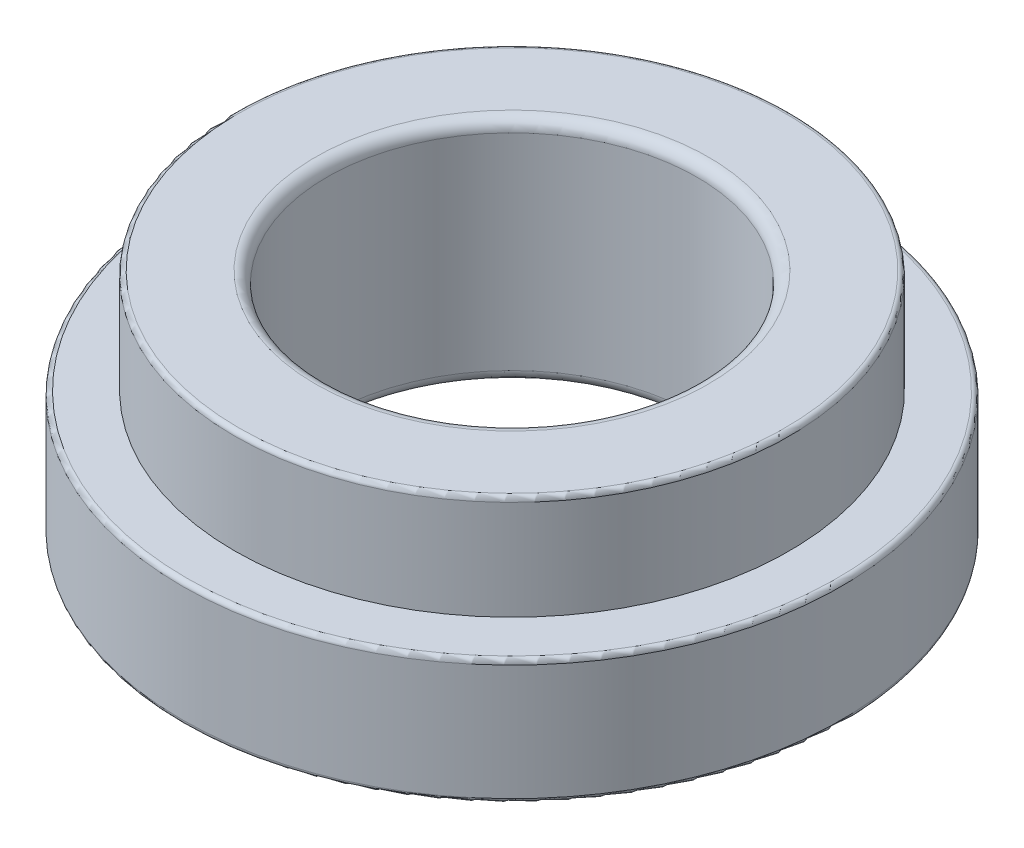
SolidWorks part; units mm, degrees
material "PE High Density"
ref_plane "Front" through (0, 0, 0) normal (0, 0, 1) x (1, 0, 0)
ref_plane "Top" through (0, 0, 0) normal (0, 1, 0) x (1, 0, 0)
ref_plane "Right" through (0, 0, 0) normal (1, 0, 0) x (0, 0, -1)
sketch "Sketch1" plane through (0, 0, 0) normal (0, 1, 0) x (1, 0, 0)
  circle A0 centre (0, 0) radius 7.125
  dimension "D1" = 14.25
extrude "Boss-Extrude1" add sketch "Sketch1" along normal blind 4.95
sketch "Sketch2" plane through (0, 4.95, 0) normal (0, 1, 0) x (1, 0, 0)
  circle A0 centre (0, 0) radius 4
  dimension "D1" = 8
extrude "Cut-Extrude2" cut sketch "Sketch2" against normal blind 12.25
sketch "Sketch3" plane through (0, 4.95, 0) normal (0, 1, 0) x (1, 0, 0)
  circle A0 centre (0, 0) radius 5.9988
  circle A1 centre (0, 0) radius 7.125
  circle A2 centre (0, 0) radius 7.125 construction
  dimension "D1" = 11.9976
extrude "Cut-Extrude3" cut sketch "Sketch3" against normal blind 2.25
fillet "Fillet1" radius 0.1 3 edges at (0, 4.95, 5.9988) (0, 2.7, 7.125) (0, 0, 7.125)
fillet "Fillet2" radius 0.25 2 edges at (0, 4.95, 4) (0, 0, 4)
